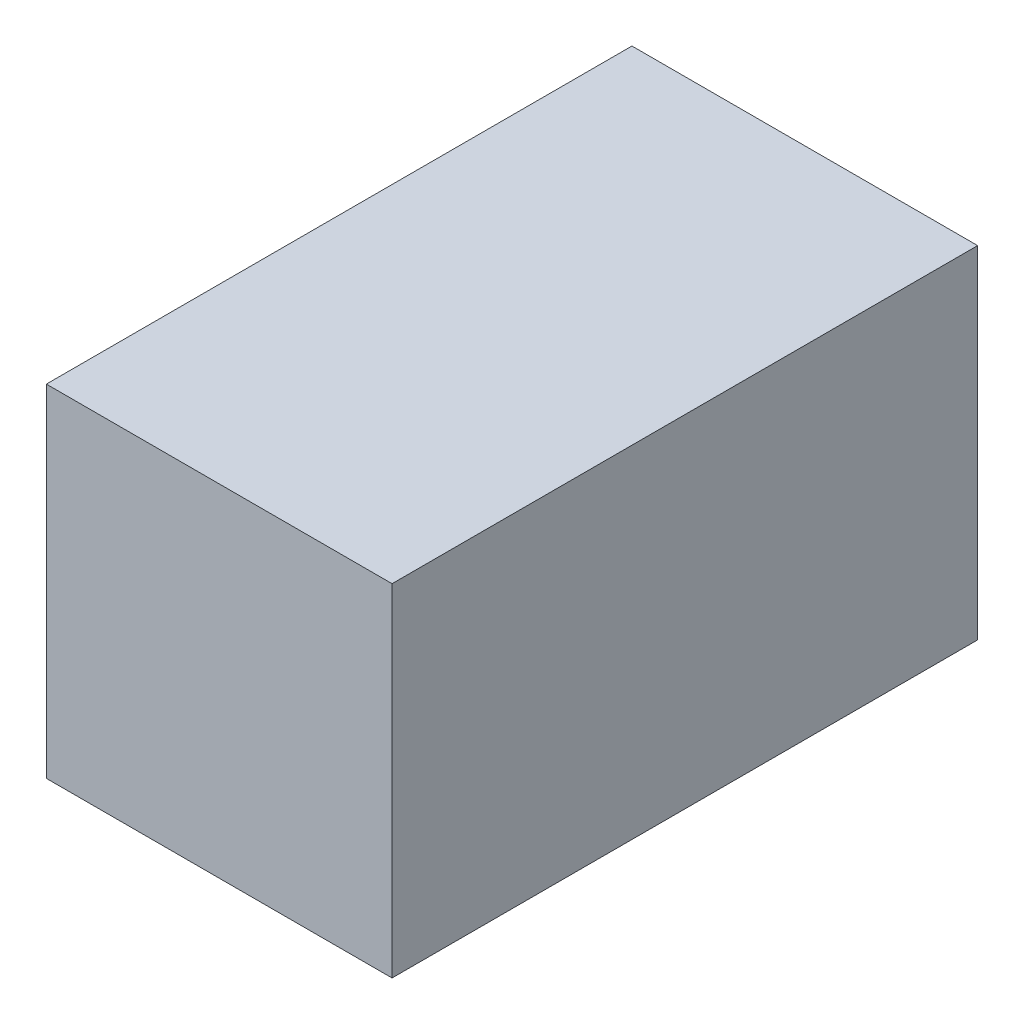
SolidWorks part; units mm, degrees
material "Custom Plastic"
ref_plane "X-Y Datum" through (0, 0, 0) normal (0, 0, 1) x (1, 0, 0)
ref_plane "X-Z Datum" through (0, 0, 0) normal (0, 1, 0) x (1, 0, 0)
ref_plane "Y-Z Datum" through (0, 0, 0) normal (1, 0, 0) x (0, 0, -1)
sketch "Sketch1" plane through (0, 0, 0) normal (0, 0, 1) x (1, 0, 0)
  line L1 (-36.5125, 36.068) -> (36.5125, 36.068)
  line L2 (-36.5125, 36.068) -> (-36.5125, -36.068)
  line L3 (-36.5125, -36.068) -> (36.5125, -36.068)
  line L4 (36.5125, 36.068) -> (36.5125, -36.068)
  line L5 (-36.5125, 36.068) -> (36.5125, -36.068) construction
  line L6 (-36.5125, -36.068) -> (36.5125, 36.068) construction
  circle A0 centre (0, -23.608) radius 8.388 construction
  point P0 (0, 0)
  dimension "D1" = 73.025
  dimension "D2" = 72.136
extrude "Boss-Extrude1" add sketch "Sketch1" along normal blind 123.698
